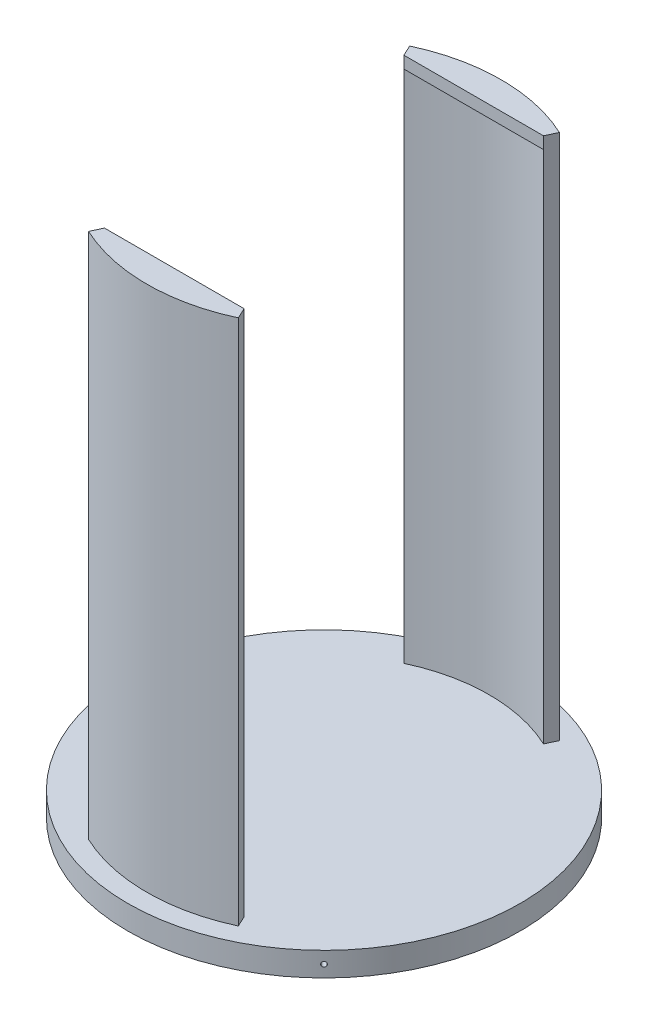
SolidWorks part; units mm, degrees
ref_plane "Front Plane" through (0, 0, 0) normal (0, 0, 1) x (1, 0, 0)
ref_plane "Top Plane" through (0, 0, 0) normal (0, 1, 0) x (1, 0, 0)
ref_plane "Right Plane" through (0, 0, 0) normal (1, 0, 0) x (0, 0, -1)
sketch "Sketch1" plane through (0, 0, 0) normal (0, 1, 0) x (1, 0, 0)
  circle A0 centre (0, 0) radius 82
  dimension "D1" = 164
extrude "Boss-Extrude1" add sketch "Sketch1" along normal blind 10
sketch "Sketch2" plane through (0, 10, 0) normal (0, 1, 0) x (1, 0, 0)
  line L0 (0, 0) -> (0, 74) construction
  line L1 (-29.1607, 62.5352) -> (-31.2738, 67.0668)
  line L2 (29.1607, 62.5352) -> (31.2738, 67.0668)
  arc A0 (29.1607, 62.5352) -> (-29.1607, 62.5352) centre (0, 0) ccw
  circle A1 centre (0, 0) radius 74 construction
  circle A2 centre (0, 0) radius 69 construction
  circle A3 centre (0, 0) radius 74
  arc A4 (31.2738, 67.0668) -> (-31.2738, 67.0668) centre (0, 0) ccw
  dimension "D3" = 25
  dimension "D4" = 25
  dimension "D1" = 8
  dimension "D2" = 5
extrude "Boss-Extrude4" add sketch "Sketch2" along normal blind 220 contours A4 L1 A0 L2
mirror "Mirror2" about plane through (0, 0, 0) normal (0, 0, 1) of "Boss-Extrude4"
sketch "Sketch4" plane through (0, 230, 0) normal (0, 1, 0) x (1, 0, 0)
  line L0 (-29.1607, 62.5352) -> (29.1607, 62.5352)
  arc A0 (-29.1607, 62.5352) -> (29.1607, 62.5352) centre (0, 0) cw
extrude "Boss-Extrude5" add sketch "Sketch4" against normal blind 5
mirror "Mirror3" about plane through (0, 0, 0) normal (0, 0, 1) of "Boss-Extrude5"
ref_plane "Plane5" through (0, 0, 0) normal (-0.7071, 0, 0.7071) x (0.7071, 0, 0.7071)
ref_plane "Plane6" through (-57.9828, 0, 57.9828) normal (-0.7071, 0, 0.7071) x (0.7071, 0, 0.7071)
sketch "Sketch7" plane through (-57.9828, 0, 57.9828) normal (-0.7071, 0, 0.7071) x (0.7071, 0, 0.7071)
  line L0 (-82, 0) -> (82, 0) construction
  circle A0 centre (0, 5) radius 1
  dimension "D1" = 2
  dimension "D2" = 5
extrude "Cut-Extrude1" cut sketch "Sketch7" against normal blind 12
pattern_circular "CirPattern1" count 4 every 90 about axis through (0, 0, 0) along (0, 1, 0) of "Cut-Extrude1"
